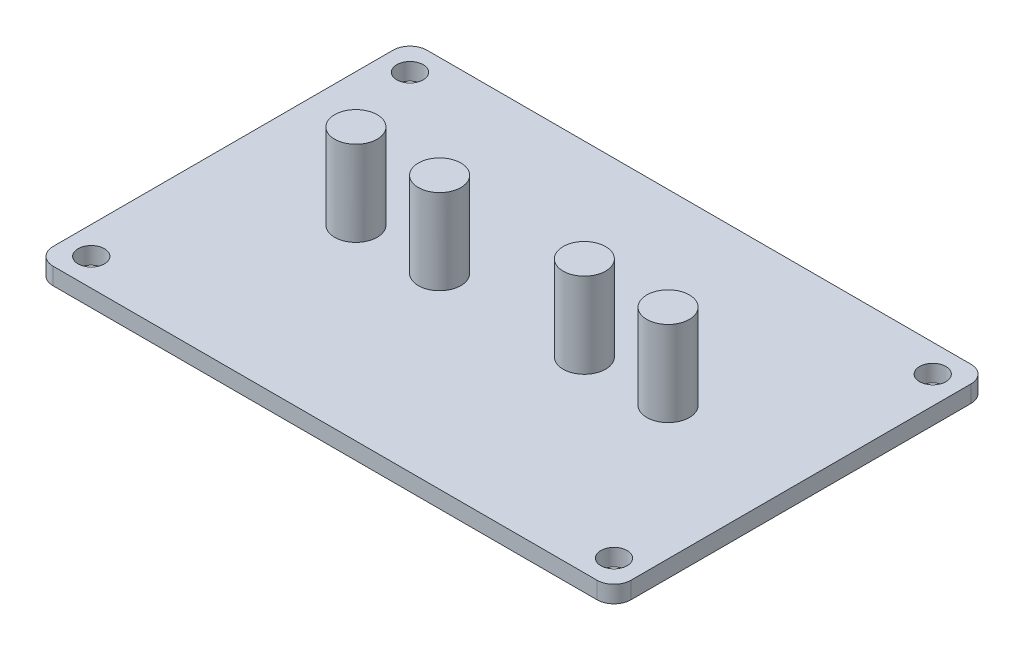
SolidWorks part; units mm, degrees
ref_plane "前视基准面" through (0, 0, 0) normal (0, 0, 1) x (1, 0, 0)
ref_plane "上视基准面" through (0, 0, 0) normal (0, 1, 0) x (1, 0, 0)
ref_plane "右视基准面" through (0, 0, 0) normal (1, 0, 0) x (0, 0, -1)
sketch "草图1" plane through (0, 0, 0) normal (0, 1, 0) x (1, 0, 0)
  line L1 (-34, -22) -> (34, -22)
  line L2 (-34, -22) -> (-34, 22)
  line L3 (-34, 22) -> (34, 22)
  line L4 (34, -22) -> (34, 22)
  line L5 (-34, -22) -> (34, 22) construction
  line L6 (-34, 22) -> (34, -22) construction
  point P0 (0, 0)
  dimension "D1" = 68
  dimension "D2" = 44
extrude "凸台-拉伸1" add sketch "草图1" along normal blind 2
sketch "草图2" plane through (0, 2, 0) normal (0, 1, 0) x (1, 0, 0)
  line L0 (0, 0) -> (0, 12.813) construction
  circle A0 centre (-18.3621, 0) radius 2.5
  circle A1 centre (-8.5142, 0) radius 2.5
  circle A2 centre (8.5142, 0) radius 2.5
  circle A3 centre (18.3621, 0) radius 2.5
  dimension "D1" = 5
  dimension "D2" = 5
  dimension "D3" = 18.3621
  dimension "D4" = 8.5142
extrude "凸台-拉伸2" add sketch "草图2" along normal blind 10
sketch "草图4" plane through (0, 2, 0) normal (0, 1, 0) x (1, 0, 0)
  line L0 (0, 0) -> (0, 29.5933) construction
  line L1 (0, 0) -> (-44.9777, 0) construction
  circle A0 centre (-30.75, 18.75) radius 1.55
  circle A1 centre (-30.75, -18.75) radius 1.55
  circle A2 centre (30.75, -18.75) radius 1.55
  circle A3 centre (30.75, 18.75) radius 1.55
  dimension "D1" = 3.1
  dimension "D2" = 61.5
  dimension "D3" = 37.5
extrude "切除-拉伸1" cut sketch "草图4" against normal through all
fillet "圆角1" radius 2 4 edges at (-34, 1, -22) (34, 1, -22) (34, 1, 22) (-34, 1, 22)
